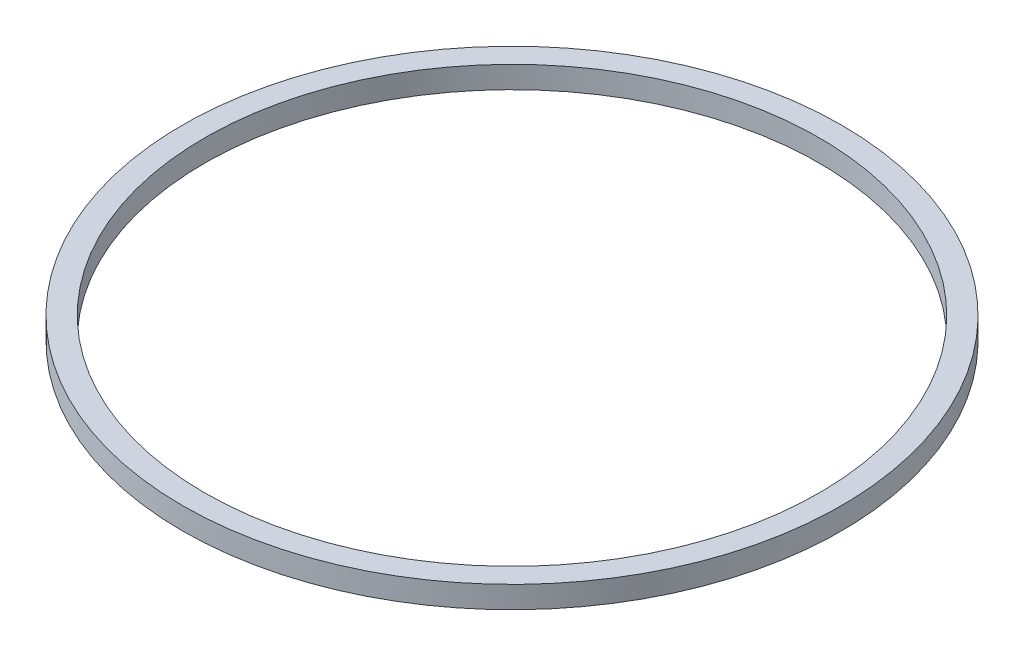
SolidWorks part; units mm, degrees
ref_plane "前视基准面" through (0, 0, 0) normal (0, 0, 1) x (1, 0, 0)
ref_plane "上视基准面" through (0, 0, 0) normal (0, 1, 0) x (1, 0, 0)
ref_plane "右视基准面" through (0, 0, 0) normal (1, 0, 0) x (0, 0, -1)
sketch "草图1" plane through (0, 0, 0) normal (0, 1, 0) x (1, 0, 0)
  circle A0 centre (0, 0) radius 190.6
  circle A1 centre (0, 0) radius 177.8
  dimension "D1" = 381.2
  dimension "D2" = 355.6
extrude "凸台-拉伸1" add sketch "草图1" along normal blind 12.7
